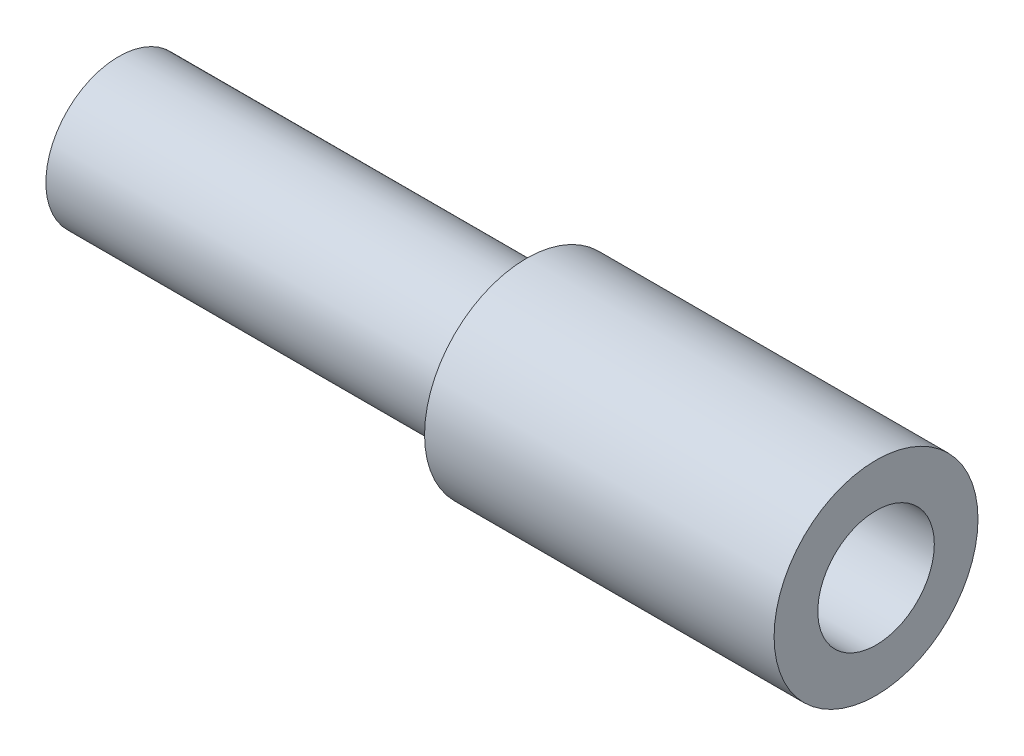
SolidWorks part; units mm, degrees
ref_plane "Płaszczyzna przednia" through (0, 0, 0) normal (0, 0, 1) x (1, 0, 0)
ref_plane "Płaszczyzna górna" through (0, 0, 0) normal (0, 1, 0) x (1, 0, 0)
ref_plane "Płaszczyzna prawa" through (0, 0, 0) normal (1, 0, 0) x (0, 0, -1)
sketch "Szkic1" plane through (0, 0, 0) normal (1, 0, 0) x (0, 0, -1)
  circle A0 centre (0, 0) radius 10
  circle A1 centre (0, 0) radius 12.5
  dimension "D1" = 20
  dimension "D2" = 25
extrude "Dodanie-wyciągnięcie1" add sketch "Szkic1" along normal blind 70
sketch "Szkic2" plane through (70, 0, 0) normal (1, 0, 0) x (0, 0, -1)
  circle A0 centre (0, 0) radius 10 construction
  circle A1 centre (0, 0) radius 10
  circle A2 centre (0, 0) radius 17.5
  dimension "D1" = 35
extrude "Dodanie-wyciągnięcie2" add sketch "Szkic2" along normal blind 60
fillet "Zaokrąglenie1" radius 0.3 1 edges at (70, 0, -12.5)
